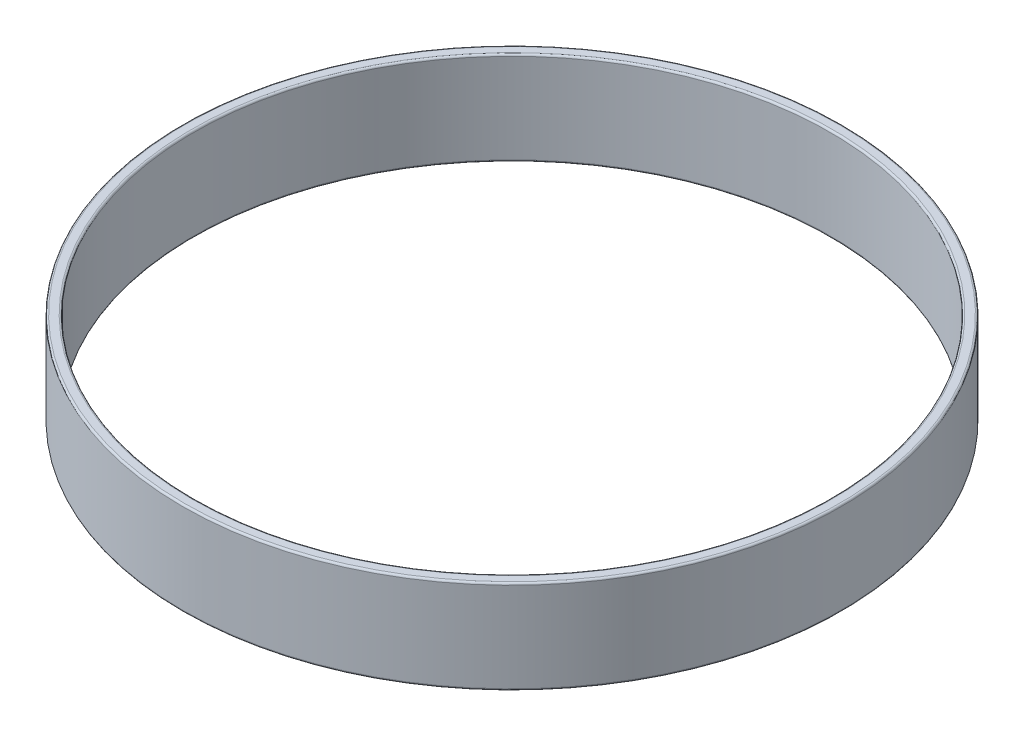
SolidWorks part; units mm, degrees
ref_plane "Front Plane" through (0, 0, 0) normal (0, 0, 1) x (1, 0, 0)
ref_plane "Top Plane" through (0, 0, 0) normal (0, 1, 0) x (1, 0, 0)
ref_plane "Right Plane" through (0, 0, 0) normal (1, 0, 0) x (0, 0, -1)
sketch "Sketch1" plane through (0, 0, 0) normal (0, 1, 0) x (1, 0, 0)
  circle A0 centre (0, 0) radius 85.25
  circle A1 centre (0, 0) radius 88.25
  dimension "D1" = 170.5
  dimension "D2" = 3
extrude "Boss-Extrude1" add sketch "Sketch1" along normal mid plane 25
fillet "Fillet1" radius 0.5 4 edges at (0, -12.5, 85.25) (0, -12.5, 88.25) (0, 12.5, 85.25) (0, 12.5, 88.25)
